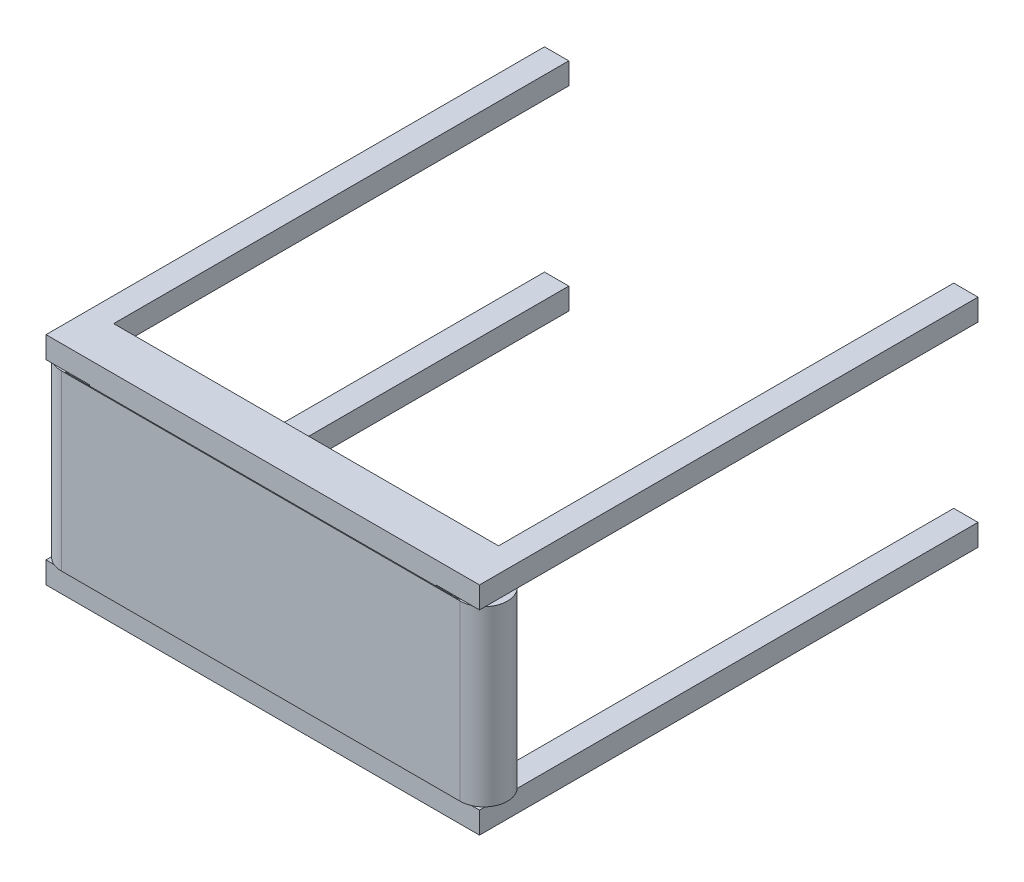
SolidWorks part; units mm, degrees
ref_plane "Front Plane" through (0, 0, 0) normal (0, 0, 1) x (1, 0, 0)
ref_plane "Top Plane" through (0, 0, 0) normal (0, 1, 0) x (1, 0, 0)
ref_plane "Right Plane" through (0, 0, 0) normal (1, 0, 0) x (0, 0, -1)
sketch "Sketch1" plane through (0, 0, 0) normal (0, 0, 1) x (1, 0, 0)
  line L0 (-500, 200) -> (-400, 200)
  line L1 (500, -250) -> (-500, -250)
  line L2 (500, -250) -> (500, -200)
  line L3 (500, 250) -> (-500, 250)
  line L4 (-500, -250) -> (-500, -200)
  line L5 (500, -250) -> (-500, 250) construction
  line L6 (500, 250) -> (-500, -250) construction
  line L7 (-400, 200) -> (-400, -200)
  line L8 (-400, -200) -> (-500, -200)
  line L9 (-500, 200) -> (-500, 250)
  line L10 (0, 250) -> (0, -250) construction
  line L11 (400, -200) -> (500, -200)
  line L12 (400, 200) -> (400, -200)
  line L13 (500, 200) -> (400, 200)
  line L14 (500, 200) -> (500, 250)
  point P0 (0, 0)
  dimension "D1" = 500
  dimension "D2" = 1000
  dimension "D3" = 100
  dimension "D4" = 50
  dimension "D5" = 50
extrude "Boss-Extrude1" add sketch "Sketch1" along normal blind 100
sketch "Sketch2" plane through (0, 200, 0) normal (0, -1, 0) x (1, 0, 0)
  line L0 (500, 100) -> (500, 0) construction
  circle A0 centre (460, 50) radius 52.5
  dimension "D1" = 105
  dimension "D2" = 40
extrude "Boss-Extrude2" add sketch "Sketch2" along normal blind 400
mirror "Mirror1" about plane through (0, 0, 0) normal (1, 0, 0) of "Boss-Extrude2"
sketch "Sketch3" plane through (0, -200, 0) normal (0, -1, 0) x (1, 0, 0)
  line L0 (-460, 102.5) -> (460, 102.5)
  line L2 (460, -2.5) -> (-512.3478, 46.0056)
  line L3 (459.9497, -4.5) -> (-514.1791, 44.0945)
  line L4 (-460, 104.5) -> (460, 104.5)
  arc A0 (-460, 102.5) -> (-512.3478, 46.0056) centre (-460, 50) ccw
  arc A1 (460, -2.5) -> (460, 102.5) centre (460, 50) ccw
  arc A2 (-460, 104.5) -> (-514.1791, 44.0945) centre (-460, 50) ccw
  arc A3 (459.9497, -4.5) -> (460, 104.5) centre (460, 50) ccw
  dimension "D1" = 105
  dimension "D2" = 105
  dimension "D3" = 2
extrude "Boss-Extrude3" add sketch "Sketch3" against normal blind 400
sketch "Sketch4" plane through (0, 0, 0) normal (0, 0, -1) x (-1, 0, 0)
  line L0 (0, 250) -> (0, 0) construction
  line L1 (-500, 250) -> (-443.9922, 250)
  line L2 (-500, 250) -> (-500, 200)
  line L3 (-500, 200) -> (-443.9922, 200)
  line L4 (-443.9922, 250) -> (-443.9922, 200)
  line L5 (-500, 250) -> (500, 250) construction
  line L6 (0, 0) -> (514.5, 0) construction
  line L7 (514.5, -200) -> (514.5, 200) construction
  line L8 (500, 200) -> (443.9922, 200)
  line L9 (443.9922, 250) -> (443.9922, 200)
  line L10 (500, 250) -> (443.9922, 250)
  line L11 (500, 250) -> (500, 200)
  line L12 (500, -250) -> (500, -200)
  line L13 (500, -250) -> (443.9922, -250)
  line L14 (443.9922, -250) -> (443.9922, -200)
  line L15 (500, -200) -> (443.9922, -200)
  line L16 (-500, -200) -> (-443.9922, -200)
  line L17 (-443.9922, -250) -> (-443.9922, -200)
  line L18 (-500, -250) -> (-443.9922, -250)
  line L19 (-500, -250) -> (-500, -200)
  dimension "D1" = 56.0078
extrude "Boss-Extrude4" add sketch "Sketch4" along normal blind 1050
